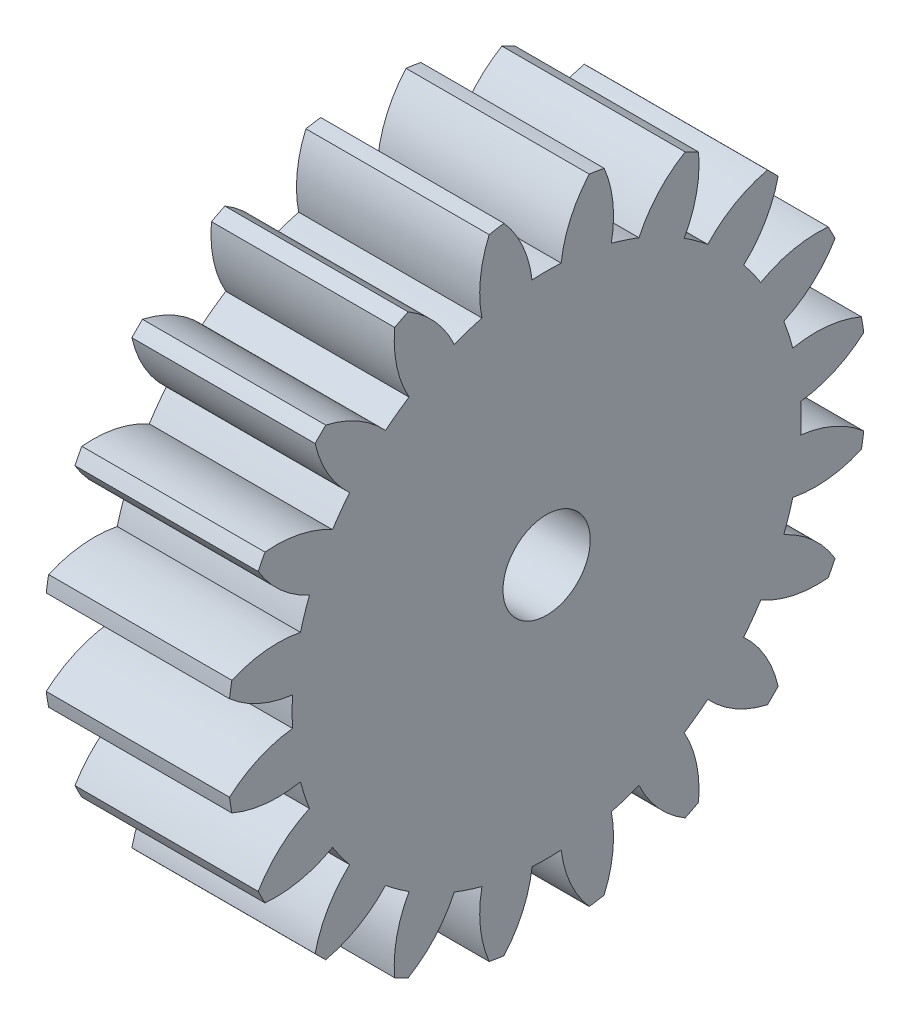
SolidWorks part; units mm, degrees
ref_plane "Plane1" through (0, 0, 0) normal (0, 0, 1) x (1, 0, 0)
ref_plane "Plane2" through (0, 0, 0) normal (0, 1, 0) x (1, 0, 0)
ref_plane "Plane3" through (0, 0, 0) normal (1, 0, 0) x (0, 0, -1)
sketch "HoldingSke" plane through (0, 0, 0) normal (0, 1, 0) x (1, 0, 0)
  line L0 (0, 0) -> (0.9397, -0.342)
  line L1 (-15, 0) -> (100, 0) construction
  line L2 (0, 0) -> (-2.1039, 2.3779)
  line L3 (0, 0) -> (-11.863, 4.5341)
  line L4 (0, 0) -> (8.1152, 2.9537)
  line L5 (0, 0) -> (-46.8476, -17.4728)
  line L6 (0, 0) -> (-5.2225, -3.5236)
  line L7 (-2.1039, 2.3779) -> (8.6586, 51.2059)
  line L8 (-76.2, 54.61) -> (-75.7, 54.61)
  line L9 (-71.009, 38.7566) -> (-53.1078, 45.2721)
  line L10 (-76.2, 71.12) -> (104.1128, 71.12)
  line L11 (0, 0) -> (-6.3, 0)
  line L12 (-76.2, 101.6) -> (-76.162, 101.6)
  line L13 (24.9733, 27.94) -> (52.9518, 28.4284)
  line L14 (24.9733, 27.94) -> (24.9743, 27.94)
  line L15 (24.9733, 27.94) -> (100.4006, 29.5858)
  line L16 (-63.627, -1) -> (-12.827, -1)
  circle A0 centre (0, 0) radius 1.5
  circle A1 centre (0, 0) radius 8.749
  circle A2 centre (0, 0) radius 37.5
  circle A3 centre (0, 0) radius 1.5
  dimension "MHD" = 17.498
  dimension "Hub_dia" = 75
  dimension "Bore" = 3
  dimension "MBD" = 3
  dimension "Num_teeth" = 20
  dimension "Pitch" = 1
  dimension "Overall_len" = 50
  dimension "Show_teeth" = 20
  dimension "Thickness" = 6.3
  dimension "OAL" = 50.0001
  dimension "T_dim" = 0.5
  dimension "Ap" = 20
  dimension "H" = 19.05
  dimension "Pitch_radius" = 180.3128
  dimension "Width" = 6.3
  dimension "Backlash" = 0.038
  dimension "Addendum_fac" = 1
  dimension "Dedendum_fac" = 1.25
  dimension "Clearance_fac" = 0.25
  dimension "Dedendum_add" = 0.001
  dimension "Module" = 1
sketch "BasProSke" plane through (0, 0, 0) normal (0, 1, 0) x (1, 0, 0)
  line L0 (-10, 0) -> (60, 0) construction
  line L1 (0, 0) -> (0, 11)
  line L2 (0, 0) -> (6.3, 0)
  line L3 (6.3, 0) -> (6.3, 11)
  line L4 (6.3, 11) -> (0, 11)
  dimension "Thickness" = 6.3
  dimension "Diameter" = 22
revolve "Base-Revolve" add sketch "BasProSke" angle 360 about L0
sketch "TooCutSke" plane through (0, 0, 0) normal (1, 0, 0) x (0, 0, -1)
  line L1 (0, 0) -> (0, 107) construction
  line L2 (0, 0) -> (-0.8511, 9.9637) construction
  line L3 (0, 0) -> (-3.1206, 19.7028) construction
  line L4 (-0.8511, 9.9637) -> (-1.5603, 9.8514) construction
  arc A0 (0.4999, 8.7347) -> (-0.4999, 8.7347) centre (0, 0) ccw
  arc A1 (1.4852, 10.9249) -> (-1.4852, 10.9249) centre (0, 0) ccw
  circle A2 centre (0, 0) radius 10 construction
  circle A3 centre (0, 0) radius 9.3969 construction
  arc A4 (-0.4999, 8.7347) -> (-1.4852, 10.9249) centre (-4.4722, 8.2645) ccw
  arc A5 (1.4852, 10.9249) -> (0.4999, 8.7347) centre (4.4722, 8.2645) ccw
  dimension "Root_dia" = 17.498
  dimension "Overcut_dia" = 22.0508
  dimension "Pitch_dia" = 20
  dimension "Base_dia" = 18.7939
  dimension "Flank_rad" = 4
  dimension "Half_ang" = 9
  dimension "Half_CT" = 0.7181
extrude "ToothCut" cut sketch "TooCutSke" along normal through all
fillet "Breaks" [suppressed] radius 0.02
fillet "RootFillets" [suppressed] radius 0.251
pattern_circular "TeethCuts" count 20 every 18 about axis through (-10, 0, 0) along (1, 0, 0) of "ToothCut", "RootFillets", "Breaks"
sketch "HubNeaOneSke" plane through (0, 0, 0) normal (-1, 0, 0) x (0, 0, 1)
  circle A0 centre (0, 0) radius 8.749
  dimension "Diameter" = 17.498
extrude "HubNearOne" [suppressed] add sketch "HubNeaOneSke" along normal blind 43.7001
sketch "HubNeaBotSke" plane through (0, 0, 0) normal (-1, 0, 0) x (0, 0, 1)
  circle A0 centre (0, 0) radius 8.749
  dimension "Diameter" = 17.498
extrude "HubNearBoth" [suppressed] add sketch "HubNeaBotSke" along normal blind 21.85
ref_plane "FarPln" through (6.3, 0, 0) normal (1, 0, 0) x (0, 0, -1)
sketch "HubFarSke" plane through (6.3, 0, 0) normal (1, 0, 0) x (0, 0, -1)
  circle A0 centre (0, 0) radius 8.749
  dimension "Diameter" = 17.498
extrude "HubFar" [suppressed] add sketch "HubFarSke" along normal blind 21.85
sketch "BorSke" plane through (0, 0, 0) normal (1, 0, 0) x (0, 0, -1)
  circle A0 centre (0, 0) radius 1.5
  dimension "Diameter" = 3
extrude "Bore" cut sketch "BorSke" along normal mid plane 100.0001
sketch "KeySke" plane through (0, 0, 0) normal (1, 0, 0) x (0, 0, -1)
  line L0 (-0.6, 0) -> (-0.6, 2)
  line L1 (-0.6, 2) -> (0.6, 2)
  line L2 (0.6, 2) -> (0.6, 0)
  line L3 (0, 0) -> (0, 34) construction
  line L4 (-0.6, 0) -> (0.6, 0)
  dimension "Offset" = 2
  dimension "Width" = 1.2
extrude "Keyway" [suppressed] cut sketch "KeySke" along normal mid plane 100.0001
pattern_circular "Keyway2" [suppressed] count 2 every 90 about axis through (-10, 0, 0) along (1, 0, 0)
equation "' \"Module@HoldingSke\" = 6.35"
equation "' \"Num_teeth@HoldingSke\" = 12"
equation "' \"Ap@HoldingSke\" =  20"
equation "' \"Ap@HoldingSke\" = 20"
equation "' \"Width@HoldingSke\" = 0.5 * 25.4"
equation "' \"Hub_dia@HoldingSke\"= 1 * 25.4"
equation "' \"Hub_dia@HoldingSke\" = 1 * 25.4"
equation "' \"Overall_len@HoldingSke\" = 1.0 * 25.4"
equation "' \"Bore@HoldingSke\" = 0.75 * 25.4"
equation "' \"T_dim@HoldingSke\" = 0.1 * 25.4"
equation "' \"Width@KeySke\" = 0.25 * 25.4"
equation "' \"Show_teeth@HoldingSke\" = 13"
equation "' \"Backlash@HoldingSke\" = 0.009 * 25.4"
equation "' \"Addendum_fac@HoldingSke\" = 1.0"
equation "' \"Dedendum_fac@HoldingSke\" = 1.25"
equation "' \"Dedendum_add@HoldingSke\" = 0.00005 * 25.4"
equation "' \"Clearance_fac@HoldingSke\" = 0.25"
equation "\"Pitch@HoldingSke\" = 1 / \"Module@HoldingSke\""
equation "\"Overcut_dia@TooCutSke\" = (\"Num_teeth@HoldingSke\" + 2 * \"Addendum_fac@HoldingSke\") / \"Pitch@HoldingSke\" + 0.002 * 25.4"
equation "\"Pitch_dia@TooCutSke\" = \"Num_teeth@HoldingSke\" / \"Pitch@HoldingSke\""
equation "\"Base_dia@TooCutSke\" = \"Num_teeth@HoldingSke\" / \"Pitch@HoldingSke\" * cos((\"Ap@HoldingSke\"  * 3.14159265 / 180))"
equation "\"Root_dia@TooCutSke\" = (\"Num_teeth@HoldingSke\" + 2) / \"Pitch@HoldingSke\" - 2 * (\"Addendum_fac@HoldingSke\" + \"Dedendum_fac@HoldingSke\") / \"Pitch@HoldingSke\" - \"Dedendum_add@HoldingSke\" * 2"
equation "\"Half_ang@TooCutSke\" = 180 / \"Num_teeth@HoldingSke\""
equation "\"Half_CT@TooCutSke\" = \"Num_teeth@HoldingSke\" / \"Pitch@HoldingSke\" * sin((3.14159265 / 2 / \"Num_teeth@HoldingSke\")) / 2 - 7 * \"Backlash@HoldingSke\" / 4"
equation "\"Flank_rad@TooCutSke\" = \"Num_teeth@HoldingSke\" / \"Pitch@HoldingSke\" / 5"
equation "\"Radius@RootFillets\" = \"Clearance_fac@HoldingSke\" / \"Pitch@HoldingSke\" + \"Dedendum_add@HoldingSke\""
equation "\"Break_rad@Breaks\" = 0.02 / \"Pitch@HoldingSke\""
equation "\"Thickness@HoldingSke\" = \"Width@HoldingSke\""
equation "\"OAL@HoldingSke\" = \"Thickness@HoldingSke\""
equation "\"MHD@HoldingSke\" = (\"Num_teeth@HoldingSke\" + 2) / \"Pitch@HoldingSke\" - 2 * (\"Addendum_fac@HoldingSke\" + \"Dedendum_fac@HoldingSke\")  / \"Pitch@HoldingSke\" - \"Dedendum_add@HoldingSke\" * 2"
equation "\"MBD@HoldingSke\" = (\"Num_teeth@HoldingSke\" + 2) / \"Pitch@HoldingSke\" - 2 * (\"Addendum_fac@HoldingSke\" + \"Dedendum_fac@HoldingSke\")  / \"Pitch@HoldingSke\" - \"Dedendum_add@HoldingSke\" * 2 - 0.002 * 25.4"
equation "\"MHD@HoldingSke\" = ((sgn( \"MHD@HoldingSke\" - \"Hub_dia@HoldingSke\" )-1)*( \"MHD@HoldingSke\" - \"Hub_dia@HoldingSke\" ))/-2+ \"Hub_dia@HoldingSke\""
equation "\"MBD@HoldingSke\" = ((sgn( \"MBD@HoldingSke\" - \"Bore@HoldingSke\" )-1)*( \"MBD@HoldingSke\" - \"Bore@HoldingSke\" ))/-2+ \"Bore@HoldingSke\""
equation "\"OAL@HoldingSke\" = ((sgn( \"OAL@HoldingSke\" - \"Overall_len@HoldingSke\" )+1)*( \"OAL@HoldingSke\" - \"Overall_len@HoldingSke\" ))/2 + \"Overall_len@HoldingSke\" + 0.000002 * 25.4"
equation "\"Num_teeth@TeethCuts\" = int( \"Show_teeth@HoldingSke\" ) + 1"
equation "\"Num_teeth@TeethCuts\" = ((sgn( \"Num_teeth@TeethCuts\" - \"Num_teeth@HoldingSke\" )-1)*( \"Num_teeth@TeethCuts\" - \"Num_teeth@HoldingSke\" ))/-2+ \"Num_teeth@HoldingSke\""
equation "\"Num_teeth@TeethCuts\" = ((sgn( \"Num_teeth@TeethCuts\" - 2.0)+1)*( \"Num_teeth@TeethCuts\" - 2.0))/2 +2.0"
equation "\"Angle@TeethCuts\" = 360.0 / \"Num_teeth@HoldingSke\""
equation "\"Diameter@BasProSke\" = (\"Num_teeth@HoldingSke\" + 2 * \"Addendum_fac@HoldingSke\") / \"Pitch@HoldingSke\""
equation "\"Thickness@BasProSke\"  = \"Thickness@HoldingSke\""
equation "' \"Fillet_rad@BasProSke\" =  \"Thickness@HoldingSke\" * 0.05"
equation "' \"Fillet_rad@BasProSke\" = \"Thickness@HoldingSke\" * 0.05"
equation "\"MHD@HoldingSke\" = ((sgn( \"MHD@HoldingSke\" - \"Root_dia@TooCutSke\" )-1)*( \"MHD@HoldingSke\" - \"Root_dia@TooCutSke\" ))/-2+ \"Root_dia@TooCutSke\""
equation "\"Diameter@HubNeaOneSke\" = \"MHD@HoldingSke\""
equation "\"Length@HubNearOne\" = \"OAL@HoldingSke\" - \"Thickness@BasProSke\""
equation "\"Diameter@HubNeaBotSke\" = \"MHD@HoldingSke\""
equation "\"Length@HubNearBoth\" = ( \"OAL@HoldingSke\" - \"Thickness@BasProSke\" ) / 2.0"
equation "\"Thickness@FarPln\" = \"Thickness@BasProSke\""
equation "\"Diameter@HubFarSke\" = \"MHD@HoldingSke\""
equation "\"Length@HubFar\" = ( \"OAL@HoldingSke\" - \"Thickness@BasProSke\" ) / 2.0"
equation "\"Diameter@BorSke\" = \"MBD@HoldingSke\""
equation "\"D1@Bore\" = \"OAL@HoldingSke\" * 2.0"
equation "\"D1@Keyway\" = \"OAL@HoldingSke\" * 2.0"
equation "\"Offset@KeySke\" = \"T_dim@HoldingSke\" + \"MBD@HoldingSke\" / 2.0"
